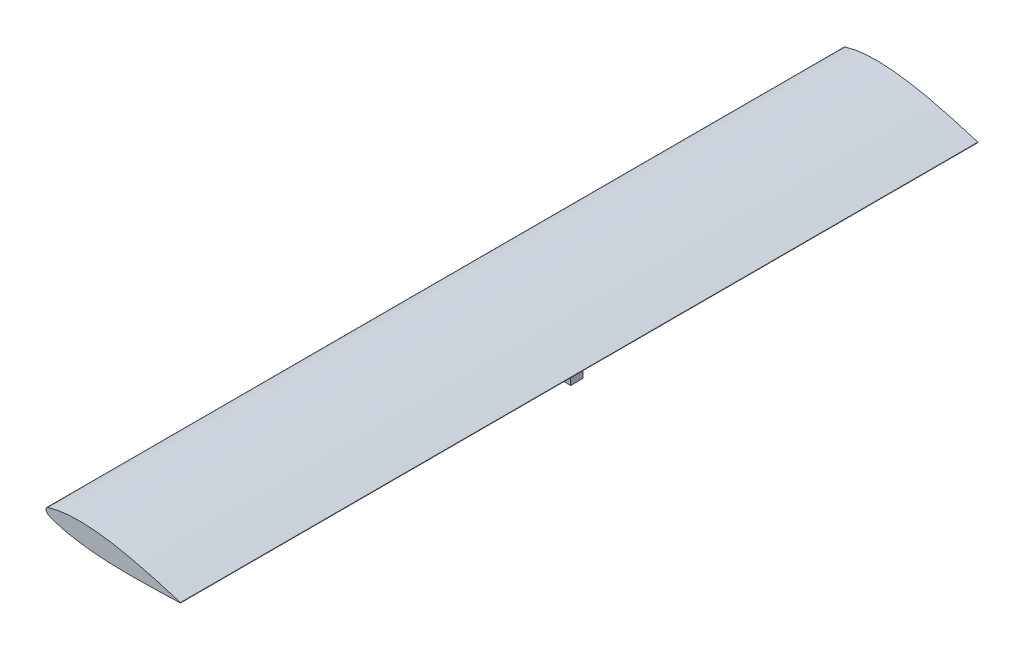
SolidWorks part; units mm, degrees
ref_plane "Front Plane" through (0, 0, 0) normal (0, 0, 1) x (1, 0, 0)
ref_plane "Top Plane" through (0, 0, 0) normal (0, 1, 0) x (1, 0, 0)
ref_plane "Right Plane" through (0, 0, 0) normal (1, 0, 0) x (0, 0, -1)
sketch "Sketch2" plane through (0, 0, 0) normal (0, 0, 1) x (1, 0, 0)
  spline S0 degree 3 poles (3.1312, 5.5493) (72.8346, 27.4331) (171.2806, 3.7257) (270.8407, -27.1695) knots 0 0 0 0 1 1 1 1
  spline S1 degree 3 poles (9.2905, -9.081) (82.8889, -36.5545) (198.0998, -28.7821) (270.8407, -27.1695) knots 0 0 0 0 1 1 1 1
  spline S2 degree 3 poles (3.1312, 5.5493) (-1.8334, 3.9906) (-1.8866, -4.9088) (9.2905, -9.081) knots 0 0 0 0 1 1 1 1
extrude "Boss-Extrude1" add sketch "Sketch2" along normal blind 1590 contours S0 S2 S1
fillet "Fillet1" radius 0.5 1 edges at (270.8407, -27.1695, 795)
sketch "Sketch3" plane through (0, 0, 0) normal (0, 1, 0) x (1, 0, 0)
  line L4 (13.5336, -807.5) -> (263.5336, -807.5)
  line L5 (13.5336, -807.5) -> (13.5336, -782.5)
  line L6 (13.5336, -782.5) -> (263.5336, -782.5)
  line L7 (263.5336, -807.5) -> (263.5336, -782.5)
  line L8 (13.5336, -807.5) -> (263.5336, -782.5) construction
  line L9 (13.5336, -782.5) -> (263.5336, -807.5) construction
  point P6 (138.5336, -795)
  dimension "D1" = 250
  dimension "D2" = 25
ref_plane "Plane1" through (0, -45, 0) normal (0, 1, 0) x (1, 0, 0)
sketch "Sketch6" plane through (0, -45, 0) normal (0, 1, 0) x (1, 0, 0)
  line L4 (263.5336, -807.5) -> (13.5336, -807.5)
  line L5 (13.5336, -807.5) -> (13.5336, -782.5)
  line L6 (13.5336, -782.5) -> (263.5336, -782.5)
  line L7 (263.5336, -782.5) -> (263.5336, -807.5)
extrude "Boss-Extrude2" add sketch "Sketch6" along normal up to next
